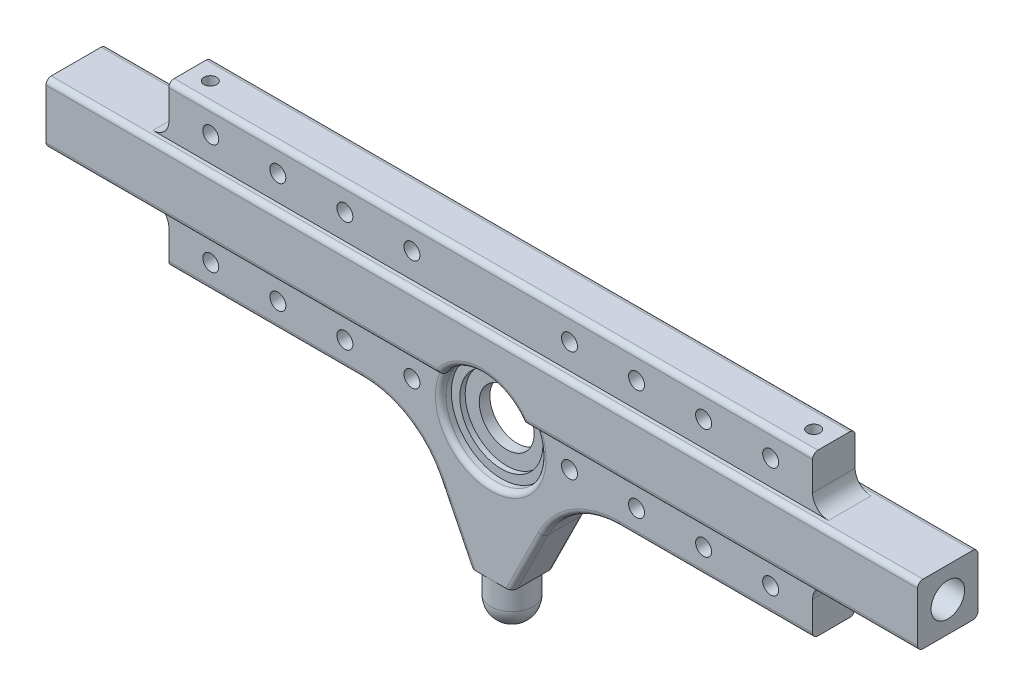
SolidWorks part; units mm, degrees
material "Cast Stainless Steel"
ref_plane "Front" through (0, 0, 0) normal (0, 0, 1) x (1, 0, 0)
ref_plane "Top" through (0, 0, 0) normal (0, 1, 0) x (1, 0, 0)
ref_plane "Right" through (0, 0, 0) normal (1, 0, 0) x (0, 0, -1)
sketch "Sketch2" plane through (0, 0, 0) normal (1, 0, 0) x (0, 0, -1)
  line L0 (-9, 18) -> (9, 18)
  line L1 (-9, 0) -> (9, 0)
  line L2 (-9, 0) -> (-9, 18)
  line L4 (9, 0) -> (9, 18)
  point P5 (0, 19.177)
  dimension "D1" = 18
  dimension "D2" = 18
extrude "Boss-Extrude2" add sketch "Sketch2" along normal mid plane 260
sketch "Sketch3" plane through (0, 0, 0) normal (0, 0, 1) x (1, 0, 0)
  line L0 (0, 0) -> (0, -47.625) construction
  line L1 (-6.35, -47.625) -> (6.35, -47.625)
  line L2 (130, 0) -> (-130, 0) construction
  line L3 (6.35, -47.625) -> (30, 0)
  line L4 (-6.35, -47.625) -> (-30, 0)
  line L5 (30, 0) -> (-30, 0)
  line L7 (-127, 0) -> (127, 0) construction
  line L8 (130, 18) -> (-130, 18) construction
  point P7 (44.831, 0)
  point P22 (0, -8.1915)
  dimension "D4" = 30
  dimension "D8" = 26.1915
  dimension "D2" = 12.7
  dimension "D3" = 44.831
  dimension "D9" = 254
extrude "Boss-Extrude3" add sketch "Sketch3" along normal mid plane 12.7
ref_plane "Plane2" through (0, -8.255, 0) normal (0, -1, 0) x (-1, 0, 0)
sketch "Sketch4" plane through (0, -8.255, 0) normal (0, -1, 0) x (-1, 0, 0)
  line L0 (-8.1915, 0) -> (8.1915, 0) construction
  line L3 (10.1534, 1.5875) -> (11.6205, 1.5875)
  line L4 (12.3825, 1.778) -> (12.3825, 2.667)
  line L5 (12.6365, 3.175) -> (14.1605, 3.175)
  line L6 (-30, 6.35) -> (30, 6.35) construction
  line L7 (-30, 6.35) -> (30, 6.35) construction
  line L8 (14.9225, 3.683) -> (14.9225, 9.0424)
  line L9 (12.3825, -1.778) -> (12.3825, -1.5875)
  line L10 (14.9225, 9.0424) -> (0, 9.0424)
  line L11 (0, 9.0424) -> (0, -9.0424)
  line L12 (14.9225, -3.683) -> (14.9225, -9.0424)
  line L13 (12.6365, -3.175) -> (14.1605, -3.175)
  line L14 (12.3825, -1.778) -> (12.3825, -2.667)
  line L15 (10.1534, -1.5875) -> (11.6205, -1.5875)
  line L16 (10.1534, 1.5875) -> (8.1915, 1.5875)
  line L17 (0, -9.0424) -> (14.9225, -9.0424)
  line L18 (11.6205, -1.5875) -> (12.3825, -1.5875)
  line L19 (14.9225, -3.683) -> (14.9225, -3.175)
  line L20 (14.9225, -3.175) -> (14.1605, -3.175)
  line L21 (11.6205, 1.5875) -> (12.3825, 1.5875)
  line L22 (12.3825, 1.5875) -> (12.3825, 1.778)
  line L23 (14.1605, 3.175) -> (14.9225, 3.175)
  line L24 (14.9225, 3.175) -> (14.9225, 3.683)
  line L27 (10.1534, -1.5875) -> (8.1915, -1.5875)
  line L29 (12.3825, -2.667) -> (12.3825, -3.175)
  line L30 (12.3825, -3.175) -> (12.6365, -3.175)
  line L31 (12.6365, 3.175) -> (12.3825, 3.175)
  line L32 (12.3825, 3.175) -> (12.3825, 2.667)
  line L33 (8.1915, 1.5875) -> (8.1915, -1.5875)
  point P14 (14.9225, 3.175)
  point P17 (12.3825, 3.175)
  point P20 (12.3825, 1.5875)
  point P49 (0, 0)
  point P50 (10.0965, -1.27)
  point P51 (12.3825, -1.5875)
  point P52 (12.3825, -3.175)
  point P53 (14.9225, -3.175)
  dimension "D1" = 12.3825
  dimension "D2" = 8.1915
  dimension "D3" = 1.5875
  dimension "D4" = 3.175
  dimension "D7" = 2.54
revolve "Cut-Revolve1" cut sketch "Sketch4" angle 360 about L11
sketch "Sketch6" plane through (130, 0, 0) normal (1, 0, 0) x (0, 0, -1)
  line L2 (-9, 0) -> (9, 0) construction
  line L7 (9, 0) -> (9, 18) construction
  circle A0 centre (0, 9) radius 5
  point P7 (0, 14)
  point P13 (5, 9)
  point P14 (9, 7.4147)
  dimension "D1" = 10
  dimension "D2" = 9
sketch "Sketch11" plane through (0, 0, 6.35) normal (0, 0, 1) x (1, 0, 0)
  line L0 (-30, 0) -> (-6.35, -47.625) construction
  line L1 (-96, 0) -> (-22.5512, 0)
  line L2 (-96, 0) -> (-96, -15)
  line L3 (-96, -15) -> (-22.5512, -15)
  line L4 (-22.5512, 0) -> (-22.5512, -15)
  line L5 (6.35, -47.625) -> (30, 0) construction
  line L6 (96, 0) -> (22.5512, 0)
  line L7 (96, 0) -> (96, -15)
  line L8 (96, -15) -> (22.5512, -15)
  line L9 (22.5512, 0) -> (22.5512, -15)
  line L11 (-96, 18) -> (-65.9033, 18)
  line L12 (-96, 18) -> (-96, 33)
  line L13 (76, 33) -> (-76, 33)
  line L14 (96, 18) -> (-96, 18)
  line L20 (-96, 0) -> (-12.4313, 0)
  line L21 (12.4313, 0) -> (96, 0)
  line L27 (96, 18) -> (-96, 18)
  line L28 (96, 0) -> (96, 18)
  line L29 (96, 0) -> (96, 18)
  line L33 (-96, 0) -> (-12.4313, 0)
  line L34 (12.4313, 0) -> (96, 0)
  line L39 (-96, 33) -> (-76, 33)
  line L40 (96, 18) -> (96, 33)
  line L41 (96, 33) -> (76, 33)
  line L50 (-96, 18) -> (-96, 0)
  line L51 (-96, 18) -> (-96, 0)
  arc A1 (12.4313, 0) -> (-12.4313, 0) centre (0, -8.255) ccw
  arc A2 (12.4313, 0) -> (-12.4313, 0) centre (0, -8.255) ccw
  dimension "D2" = 15
  dimension "D3" = 15
  dimension "D5" = 15
  dimension "D6" = 15
  dimension "D7" = 20
  dimension "D9" = 20
  dimension "D1" = 0
extrude "Boss-Extrude6" add sketch "Sketch11" against normal blind 12.7
sketch "Sketch12" plane through (0, 0, 0) normal (0, 0, 1) x (1, 0, 0)
  line L0 (-6.35, -47.625) -> (6.35, -47.625) construction
  line L1 (0, -47.625) -> (6.35, -47.625)
  line L3 (6.35, -47.625) -> (6.35, -54.61)
  line L4 (0, -54.61) -> (0, -60.96) construction
  line L5 (0, -60.96) -> (0, -47.625)
  arc A0 (0, -60.96) -> (6.35, -54.61) centre (0, -54.61) ccw
  dimension "D1" = 6.985
  dimension "D2" = 6.35
revolve "Revolve2" add sketch "Sketch12" angle 360 about L4
sketch "Sketch13" plane through (0, 0, 6.35) normal (0, 0, 1) x (1, 0, 0)
  line L0 (96, -7.5) -> (66.7795, -7.5) construction
  line L1 (0, -54.5316) -> (0, 44.2934) construction
  line L2 (-96, 33) -> (96, 33) construction
  line L3 (96, 18) -> (96, 33) construction
  line L4 (-96, 18) -> (-96, 33) construction
  line L5 (83.5, -7.5) -> (83.5, 25.5) construction
  line L6 (83.5, 9) -> (-83.5, 9) construction
  line L9 (96, 0) -> (12.4313, 0)
  line L10 (-12.4313, 0) -> (-96, 0)
  line L11 (-96, 0) -> (-96, -15)
  line L12 (-96, -15) -> (-22.5512, -15)
  line L13 (-22.5512, -15) -> (-6.35, -47.625)
  line L14 (-6.35, -47.625) -> (0, -47.625)
  line L15 (6.35, -47.625) -> (22.5512, -15)
  line L16 (22.5512, -15) -> (96, -15)
  line L17 (96, -15) -> (96, 0)
  line L18 (96, 0) -> (12.4313, 0)
  line L19 (-12.4313, 0) -> (-96, 0)
  line L20 (-96, 0) -> (-96, -15)
  line L21 (-96, -15) -> (-22.5512, -15)
  line L22 (-22.5512, -15) -> (-6.35, -47.625)
  line L23 (-6.35, -47.625) -> (0, -47.625)
  line L24 (6.35, -47.625) -> (22.5512, -15)
  line L25 (22.5512, -15) -> (96, -15)
  line L26 (96, -15) -> (96, 0)
  line L31 (0, -47.625) -> (6.35, -47.625)
  line L32 (0, -47.625) -> (6.35, -47.625)
  circle A0 centre (83.5, -7.5) radius 2.3813
  circle A1 centre (63.5, -7.5) radius 2.3813
  arc A2 (-12.4313, 0) -> (12.4313, 0) centre (0, -8.255) ccw
  arc A3 (-12.4313, 0) -> (12.4313, 0) centre (0, -8.255) ccw
  circle A4 centre (43.5, -7.5) radius 2.3812
  circle A5 centre (23.5, -7.5) radius 2.3812
  circle A6 centre (-83.5, -7.5) radius 2.3813
  circle A7 centre (-63.5, -7.5) radius 2.3813
  circle A8 centre (-43.5, -7.5) radius 2.3812
  circle A9 centre (-23.5, -7.5) radius 2.3812
  circle A10 centre (-83.5, 25.5) radius 2.3813
  circle A11 centre (83.5, 25.5) radius 2.3813
  circle A12 centre (-63.5, 25.5) radius 2.3813
  circle A13 centre (-43.5, 25.5) radius 2.3812
  circle A14 centre (-23.5, 25.5) radius 2.3812
  circle A15 centre (23.5, 25.5) radius 2.3812
  circle A16 centre (43.5, 25.5) radius 2.3812
  circle A17 centre (63.5, 25.5) radius 2.3813
  point P44 (83.5, -7.5)
  dimension "D3" = 4.7625
  dimension "D6" = 4.7625
  dimension "D7" = 12.5
  dimension "D9" = 4.7625
  dimension "D10" = 4.7625
  dimension "D2" = 12.5
  dimension "D5" = 7.5
  dimension "D8" = 12.5
  dimension "D11" = 167
  dimension "D1" = 0
  dimension "D4" = 4
extrude "Cut-Extrude3" cut sketch "Sketch13" against normal blind 14.27 contours A17 | A16 | A15 | A14 | A13 | A12 | A11 | A0 | A1 | A4 | A5 | A6 | A7 | A8 | A9 | A10
fillet "Fillet4" radius 25.4 2 edges at (22.5512, -15, 0) (-22.5512, -15, 0)
extrude "Cut-Extrude4" cut sketch "Sketch6" against normal blind 42
sketch "Sketch14" plane through (88, 0, 0) normal (1, 0, 0) x (0, 0, -1)
  circle A0 centre (0, 9) radius 3.9688
  dimension "D1" = 7.9375
extrude "Cut-Extrude5" cut sketch "Sketch14" against normal blind 22
sketch "Sketch15" plane through (130, 0, 0) normal (1, 0, 0) x (0, 0, -1)
  line L4 (-9, 18) -> (-9, 0)
  line L5 (-9, 18) -> (-9, 0)
  line L6 (-9, 0) -> (9, 0)
  line L7 (-9, 0) -> (9, 0)
  line L8 (9, 0) -> (9, 18)
  line L9 (9, 0) -> (9, 18)
  line L10 (9, 18) -> (-9, 18)
  line L11 (9, 18) -> (-9, 18)
  circle A0 centre (0, 9) radius 5 construction
  circle A3 centre (0, 9) radius 5
  dimension "D1" = 0
extrude "Cut-Extrude6" [suppressed] cut sketch "Sketch15" against normal blind 7
sketch "Sketch16" plane through (0, -15, 0) normal (0, -1, 0) x (1, 0, 0)
  line L0 (96, -6.35) -> (96, 6.35) construction
  circle A0 centre (90, 0) radius 1.905
  dimension "D2" = 3.81
  dimension "D1" = 6
extrude "Cut-Extrude7" cut sketch "Sketch16" against normal through all
fillet "Fillet7" radius 1.5875 14 edges at (10.9489, -38.364, -6.35) (10.9489, -38.364, 6.35) (-10.9489, -38.364, 6.35) (-10.9489, -38.364, -6.35) (-24.9142, -18.8117, 6.35) (-24.9142, -18.8117, -6.35) (24.9142, -18.8117, 6.35) (24.9142, -18.8117, -6.35) (-67.1486, -15, 6.35) (67.1486, -15, -6.35) (0, 33, -6.35) (67.1486, -15, 6.35) (-67.1486, -15, -6.35) (0, 33, 6.35)
fillet "Fillet8" radius 1.5875 10 edges at (-71.2156, 0, -9) (71.2156, 0, -9) (0, 18, -9) (71.2156, 0, 9) (-71.2156, 0, 9) (0, 18, 9) (0, -23.1775, 6.35) (0, 6.6675, 9) (0, 6.6675, -9) (0, -23.1775, -6.35)
sketch "Sketch18" plane through (0, 0, 9) normal (0, 0, 1) x (1, 0, 0)
  line L55 (-98.54, 20.54) -> (-98.54, 31.4125)
  line L56 (-98.54, 35.54) -> (-98.54, 31.4125)
  line L57 (-98.54, 35.54) -> (-78.4479, 35.54)
  line L58 (-76.1164, 33.2086) -> (-78.4479, 35.54)
  line L59 (-66.4237, 23.5158) -> (-76.1164, 33.2086)
  line L60 (-59.2395, 20.54) -> (59.2395, 20.54)
  line L61 (66.4237, 23.5158) -> (76.1164, 33.2086)
  line L62 (78.4479, 35.54) -> (76.1164, 33.2086)
  line L63 (78.4479, 35.54) -> (98.54, 35.54)
  line L64 (98.54, 31.4125) -> (98.54, 35.54)
  line L65 (98.54, 20.54) -> (98.54, 31.4125)
  line L66 (125.54, 20.54) -> (98.54, 20.54)
  line L67 (125.54, -2.54) -> (125.54, 20.54)
  line L68 (98.54, -2.54) -> (125.54, -2.54)
  line L69 (98.54, -2.54) -> (98.54, -13.4125)
  line L70 (98.54, -17.54) -> (98.54, -13.4125)
  line L71 (98.54, -17.54) -> (38.2973, -17.54)
  line L72 (17.8228, -30.2326) -> (8.89, -48.2209)
  line L73 (8.89, -54.61) -> (8.89, -48.2209)
  line L74 (-8.89, -48.2209) -> (-8.89, -54.61)
  line L75 (-8.89, -48.2209) -> (-17.8228, -30.2326)
  line L76 (-38.2973, -17.54) -> (-98.54, -17.54)
  line L77 (-98.54, -13.4125) -> (-98.54, -17.54)
  line L78 (-98.54, -2.54) -> (-98.54, -13.4125)
  line L79 (-125.54, -2.54) -> (-98.54, -2.54)
  line L80 (-125.54, 20.54) -> (-125.54, -2.54)
  line L81 (-98.54, 20.54) -> (-125.54, 20.54)
  arc A10 (-66.4237, 23.5158) -> (-59.2395, 20.54) centre (-59.2395, 30.7) ccw
  arc A11 (59.2395, 20.54) -> (66.4237, 23.5158) centre (59.2395, 30.7) ccw
  arc A12 (38.2973, -17.54) -> (17.8228, -30.2326) centre (38.2973, -40.4) ccw
  arc A13 (-8.89, -54.61) -> (8.89, -54.61) centre (0, -54.61) ccw
  arc A14 (-17.8228, -30.2326) -> (-38.2973, -17.54) centre (-38.2973, -40.4) ccw
sketch "Sketch19" plane through (0, -15, 0) normal (0, -1, 0) x (1, 0, 0)
  line L0 (-96, -4.7625) -> (-96, 4.7625) construction
  line L1 (-62.98, -0.9525) -> (-70.6, -0.9525)
  line L2 (-62.98, -0.9525) -> (-62.98, 0.9525)
  line L3 (-62.98, 0.9525) -> (-70.6, 0.9525)
  line L4 (-70.6, -0.9525) -> (-70.6, 0.9525)
  line L5 (-96, -4.7625) -> (-38.2973, -4.7625) construction
  line L6 (-38.2973, 4.7625) -> (-96, 4.7625) construction
  dimension "D1" = 25.4
  dimension "D2" = 3.81
  dimension "D3" = 3.81
  dimension "D4" = 7.62
extrude "Boss-Extrude7" [suppressed] add sketch "Sketch19" along normal blind 25.4
sketch "Sketch20" [suppressed] plane through (-24.0655, -11.9506, 0) normal (-0.8956, -0.4448, 0) x (0, 0, 1)
  line L0 (-4.7625, -19.1507) -> (-4.7625, -39.8309) construction
  line L1 (-0.9525, -32.2109) -> (0.9525, -32.2109)
  line L2 (-0.9525, -32.2109) -> (-0.9525, -24.5909)
  line L3 (-0.9525, -24.5909) -> (0.9525, -24.5909)
  line L4 (0.9525, -32.2109) -> (0.9525, -24.5909)
  line L5 (4.7625, -39.8309) -> (4.7625, -19.1507) construction
  line L6 (4.7625, -39.8309) -> (0, -39.8309) construction
  dimension "D1" = 3.81
  dimension "D2" = 3.81
  dimension "D3" = 7.62
  dimension "D4" = 7.62
extrude "Boss-Extrude8" [suppressed] add sketch "Sketch20" along normal blind 25.4
sketch "Sketch21" [suppressed] plane through (0, 18, 0) normal (0, 1, 0) x (1, 0, 0)
  line L0 (-59.2395, 6.35) -> (-59.2395, -6.35) construction
  line L1 (-49.0795, 1.6975) -> (-41.4595, 1.6975)
  line L2 (-49.0795, 1.6975) -> (-49.0795, -1.6975)
  line L3 (-49.0795, -1.6975) -> (-41.4595, -1.6975)
  line L4 (-41.4595, 1.6975) -> (-41.4595, -1.6975)
  line L5 (-96, -7.4125) -> (96, -7.4125) construction
  line L6 (96, 7.4125) -> (-96, 7.4125) construction
  dimension "D1" = 7.62
  dimension "D2" = 10.16
  dimension "D3" = 5.715
  dimension "D4" = 5.715
extrude "Boss-Extrude9" [suppressed] add sketch "Sketch21" along normal blind 25.4
sketch "Sketch22" [suppressed] plane through (0, 18, 0) normal (0, 1, 0) x (1, 0, 0)
  line L0 (-41.4595, 1.6975) -> (-49.0795, 1.6975) construction
  line L1 (-3.81, 1.6975) -> (3.81, 1.6975)
  line L2 (-3.81, 1.6975) -> (-3.81, -1.6975)
  line L3 (-3.81, -1.6975) -> (3.81, -1.6975)
  line L4 (3.81, 1.6975) -> (3.81, -1.6975)
  line L5 (-49.0795, -1.6975) -> (-41.4595, -1.6975) construction
  line L6 (96, 7.4125) -> (-96, 7.4125) construction
  point P8 (0, 7.4125)
  dimension "D1" = 7.62
  dimension "D2" = 0
  dimension "D3" = 0
  dimension "D4" = 3.81
extrude "Boss-Extrude10" [suppressed] add sketch "Sketch22" along normal blind 25.4
fillet "Fillet12" [suppressed] radius 6.35
fillet "Fillet13" [suppressed] radius 6.35
sketch "Sketch23" [suppressed] plane through (0, 0, -9) normal (0, 0, -1) x (-1, 0, 0)
  line L0 (98.54, 20.54) -> (98.54, -2.54)
  line L1 (-98.54, 20.54) -> (-98.54, -2.54)
  line L27 (8.89, -54.61) -> (8.89, -48.2209)
  line L28 (-8.89, -48.2209) -> (-8.89, -54.61)
  line L29 (-17.8228, -30.2326) -> (-8.89, -48.2209)
  line L30 (-98.54, -17.54) -> (-38.2973, -17.54)
  line L31 (-98.54, -13.4125) -> (-98.54, -17.54)
  line L32 (-98.54, -2.54) -> (-98.54, -13.4125)
  line L33 (-125.54, -2.54) -> (-98.54, -2.54)
  line L34 (-125.54, 20.54) -> (-125.54, -2.54)
  line L35 (-98.54, 20.54) -> (-125.54, 20.54)
  line L36 (-98.54, 31.4125) -> (-98.54, 20.54)
  line L37 (-98.54, 35.54) -> (-98.54, 31.4125)
  line L38 (-78.4479, 35.54) -> (-98.54, 35.54)
  line L39 (-76.1164, 33.2086) -> (-78.4479, 35.54)
  line L40 (-66.4237, 23.5158) -> (-76.1164, 33.2086)
  line L41 (59.2395, 20.54) -> (-59.2395, 20.54)
  line L42 (76.1164, 33.2086) -> (66.4237, 23.5158)
  line L43 (78.4479, 35.54) -> (76.1164, 33.2086)
  line L44 (98.54, 35.54) -> (78.4479, 35.54)
  line L45 (98.54, 31.4125) -> (98.54, 35.54)
  line L46 (98.54, 20.54) -> (98.54, 31.4125)
  line L47 (125.54, 20.54) -> (98.54, 20.54)
  line L48 (125.54, -2.54) -> (125.54, 20.54)
  line L49 (98.54, -2.54) -> (125.54, -2.54)
  line L50 (98.54, -13.4125) -> (98.54, -2.54)
  line L51 (98.54, -17.54) -> (98.54, -13.4125)
  line L52 (38.2973, -17.54) -> (98.54, -17.54)
  line L53 (8.89, -48.2209) -> (17.8228, -30.2326)
  line L54 (8.89, -54.61) -> (8.89, -48.2209)
  line L55 (-8.89, -48.2209) -> (-8.89, -54.61)
  line L56 (-17.8228, -30.2326) -> (-8.89, -48.2209)
  line L57 (-98.54, -17.54) -> (-38.2973, -17.54)
  line L58 (-98.54, -13.4125) -> (-98.54, -17.54)
  line L59 (-98.54, -2.54) -> (-98.54, -13.4125)
  line L63 (-98.54, 31.4125) -> (-98.54, 20.54)
  line L64 (-98.54, 35.54) -> (-98.54, 31.4125)
  line L65 (-78.4479, 35.54) -> (-98.54, 35.54)
  line L66 (-76.1164, 33.2086) -> (-78.4479, 35.54)
  line L67 (-66.4237, 23.5158) -> (-76.1164, 33.2086)
  line L68 (59.2395, 20.54) -> (-59.2395, 20.54)
  line L69 (76.1164, 33.2086) -> (66.4237, 23.5158)
  line L70 (78.4479, 35.54) -> (76.1164, 33.2086)
  line L71 (98.54, 35.54) -> (78.4479, 35.54)
  line L72 (98.54, 31.4125) -> (98.54, 35.54)
  line L73 (98.54, 20.54) -> (98.54, 31.4125)
  line L77 (98.54, -13.4125) -> (98.54, -2.54)
  line L78 (98.54, -17.54) -> (98.54, -13.4125)
  line L79 (38.2973, -17.54) -> (98.54, -17.54)
  line L80 (8.89, -48.2209) -> (17.8228, -30.2326)
  arc A5 (-8.89, -54.61) -> (8.89, -54.61) centre (0, -54.61) ccw
  arc A6 (-17.8228, -30.2326) -> (-38.2973, -17.54) centre (-38.2973, -40.4) ccw
  arc A7 (-66.4237, 23.5158) -> (-59.2395, 20.54) centre (-59.2395, 30.7) ccw
  arc A8 (59.2395, 20.54) -> (66.4237, 23.5158) centre (59.2395, 30.7) ccw
  arc A9 (38.2973, -17.54) -> (17.8228, -30.2326) centre (38.2973, -40.4) ccw
  arc A10 (-8.89, -54.61) -> (8.89, -54.61) centre (0, -54.61) ccw
  arc A11 (-17.8228, -30.2326) -> (-38.2973, -17.54) centre (-38.2973, -40.4) ccw
  arc A12 (-66.4237, 23.5158) -> (-59.2395, 20.54) centre (-59.2395, 30.7) ccw
  arc A13 (59.2395, 20.54) -> (66.4237, 23.5158) centre (59.2395, 30.7) ccw
  arc A14 (38.2973, -17.54) -> (17.8228, -30.2326) centre (38.2973, -40.4) ccw
  dimension "D1" = 0
sketch "Sketch24" plane through (0, 0, -6.35) normal (0, 0, -1) x (-1, 0, 0)
  point P0 (-83.5, -7.5)
fillet "Fillet14" [suppressed] radius 1.5875
sketch "Sketch25" [suppressed] plane through (0, 43.4, 0) normal (0, 1, 0) x (1, 0, 0)
  point P0 (-45.1971, 0)
  point P1 (0, 0)
  dimension "D1" = 45.1971
sketch "Sketch26" [suppressed] plane through (0, 0, -9) normal (0, 0, -1) x (-1, 0, 0)
  line L0 (123, 0.0703) -> (123, 17.9297) construction
  line L1 (123, 0.0703) -> (123, 17.9297)
  line L2 (-123, 17.9297) -> (-123, 0.0703) construction
  line L3 (-123, 17.9297) -> (-123, 0.0703)
  circle A0 centre (83.5, -7.5) radius 2.3813 construction
  circle A1 centre (83.5, -7.5) radius 2.3813
  circle A2 centre (-83.5, -7.5) radius 2.3813 construction
  circle A3 centre (-83.5, -7.5) radius 2.3813
  arc A4 (-6.35, -54.61) -> (6.35, -54.61) centre (0, -54.61) ccw construction
  arc A5 (-6.35, -54.61) -> (6.35, -54.61) centre (0, -54.61) ccw
  point P13 (0, -60.96)
  dimension "D1" = 39.5
  dimension "D2" = 246
  dimension "D3" = 53.46
mirror "Mirror1" about plane through (0, 0, 0) normal (1, 0, 0) of "Cut-Extrude7", "Cut-Extrude4", "Cut-Extrude5"
fillet "Fillet15" radius 4.7625 4 edges at (-96, 0, 0) (-96, 18, 0) (96, 0, 0) (96, 18, 0)
equation "\"0.0625mmin\"=0.0625"
equation "\".25i\"=0.1"
